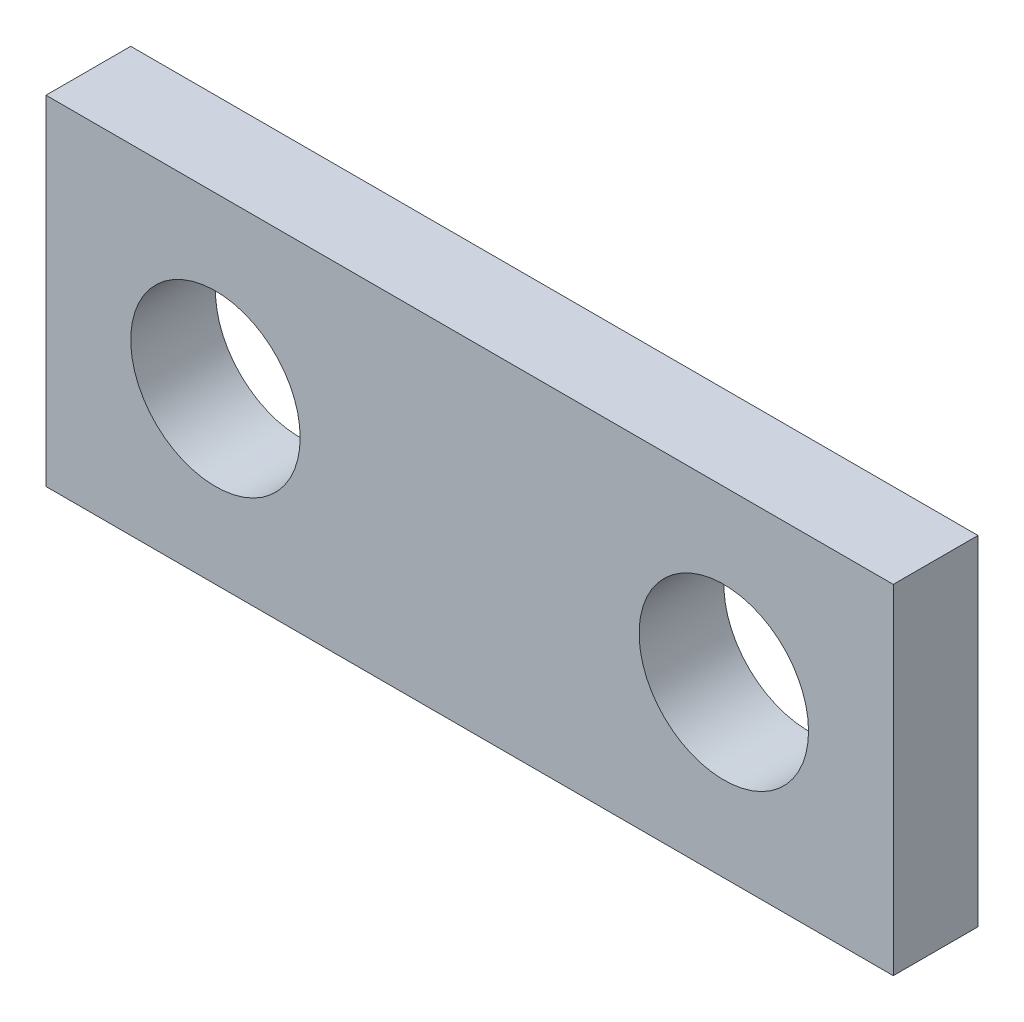
SolidWorks part; units mm, degrees
ref_plane "Front Plane" through (0, 0, 0) normal (0, 0, 1) x (1, 0, 0)
ref_plane "Top Plane" through (0, 0, 0) normal (0, 1, 0) x (1, 0, 0)
ref_plane "Right Plane" through (0, 0, 0) normal (1, 0, 0) x (0, 0, -1)
sketch "Sketch1" plane through (0, 0, 0) normal (0, 0, 1) x (1, 0, 0)
  line L0 (-15, 10) -> (-15, -10) construction
  line L1 (-25, 10) -> (25, 10)
  line L2 (-25, 10) -> (-25, -10)
  line L3 (-25, -10) -> (25, -10)
  line L4 (25, 10) -> (25, -10)
  line L5 (15, 10) -> (15, -10) construction
  circle A2 centre (15, 0) radius 5
  circle A3 centre (-15, 0) radius 5
  point P0 (0, 0)
  point P14 (15, 0)
  point P17 (-25, 0)
  point P18 (0, 10)
  dimension "D1" = 10
  dimension "D2" = 10
  dimension "D4" = 10
  dimension "D5" = 20
  dimension "D6" = 50
extrude "Boss-Extrude1" add sketch "Sketch1" along normal blind 5
